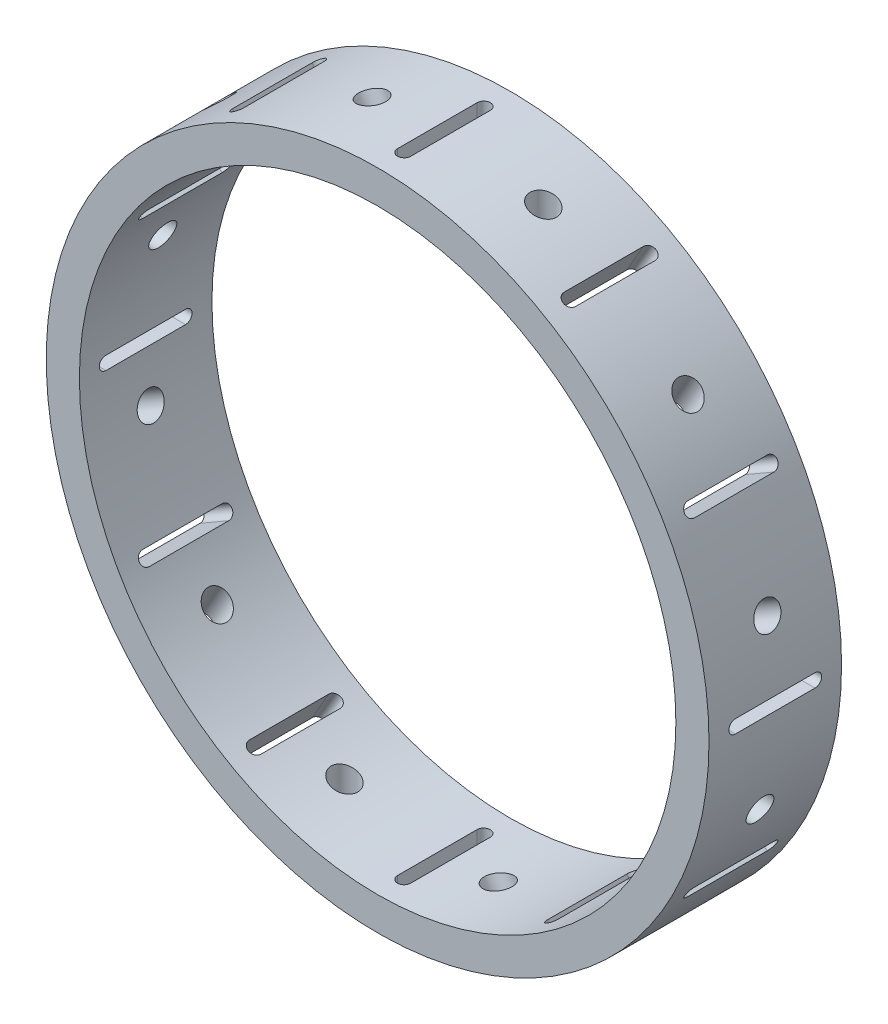
SolidWorks part; units mm, degrees
ref_plane "Front Plane" through (0, 0, 0) normal (0, 0, 1) x (1, 0, 0)
ref_plane "Top Plane" through (0, 0, 0) normal (0, 1, 0) x (1, 0, 0)
ref_plane "Right Plane" through (0, 0, 0) normal (1, 0, 0) x (0, 0, -1)
sketch "Sketch1" plane through (0, 0, 0) normal (0, 0, 1) x (1, 0, 0)
  circle A0 centre (0, 0) radius 50
  dimension "D1" = 100
extrude "Boss-Extrude1" add sketch "Sketch1" along normal mid plane 20
sketch "Sketch2" plane through (0, 0, 10) normal (0, 0, 1) x (1, 0, 0)
  circle A0 centre (0, 0) radius 45
  dimension "D1" = 90
extrude "Cut-Extrude1" cut sketch "Sketch2" against normal blind 20
ref_plane "Plane1" through (0, 50, 0) normal (0, 1, 0) x (1, 0, 0)
sketch "Sketch4" plane through (0, 50, 0) normal (0, 1, 0) x (1, 0, 0)
  line L0 (0, 6) -> (0, -6) construction
  line L1 (1, 6) -> (1, -6)
  line L2 (-1, 6) -> (-1, -6)
  arc A0 (1, 6) -> (-1, 6) centre (0, 6) ccw
  arc A1 (-1, -6) -> (1, -6) centre (0, -6) ccw
  point P2 (0, 0)
  point P8 (1, 0)
  dimension "D1" = 12
  dimension "D2" = 2
extrude "Cut-Extrude3" cut sketch "Sketch4" against normal blind 20
sketch "Sketch6" plane through (0, 50, 0) normal (0, 1, 0) x (1, 0, 0)
  line L1 (0, 20.245) -> (0, -22.3304) construction
  circle A0 centre (15, 0) radius 2
  dimension "D1" = 4
  dimension "D2" = 15
extrude "Cut-Extrude5" cut sketch "Sketch6" against normal blind 20
pattern_circular "CirPattern3" count 12 over 360 about axis through (0, 0, 0) along (0, 0, 1) of "Cut-Extrude5", "Cut-Extrude3"
